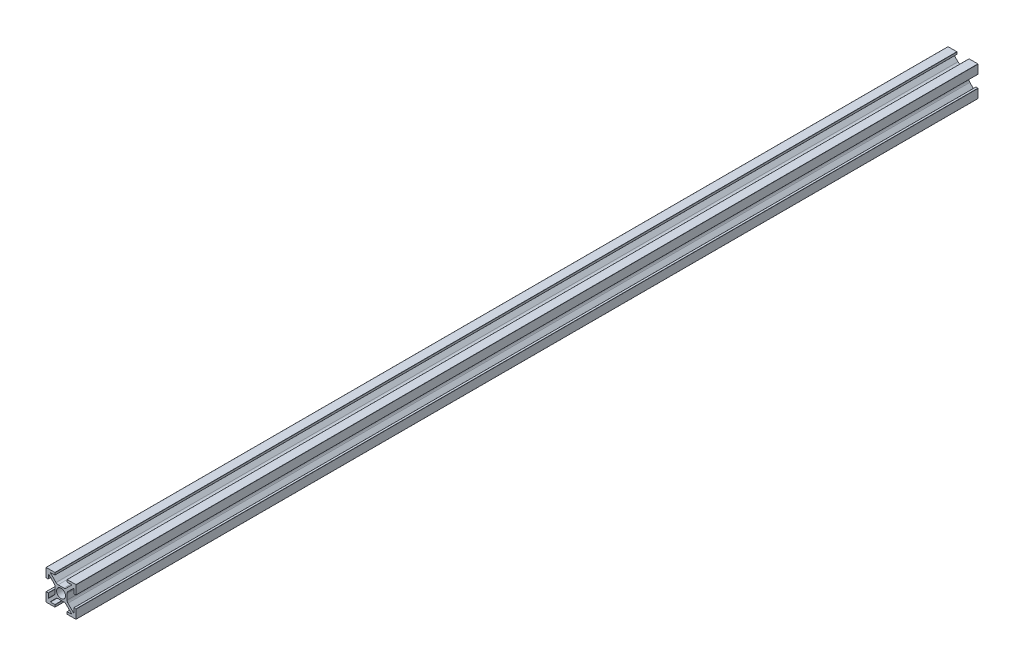
SolidWorks part; units mm, degrees
material "6061-T6 (SS)"
ref_plane "Front Plane" through (0, 0, 0) normal (0, 0, 1) x (1, 0, 0)
ref_plane "Top Plane" through (0, 0, 0) normal (0, 1, 0) x (1, 0, 0)
ref_plane "Right Plane" through (0, 0, 0) normal (1, 0, 0) x (0, 0, -1)
ref_plane "Plane1" through (0, 0, 60) normal (0, 0, 1) x (1, 0, 0)
sketch "Sketch1" plane through (0, 0, 60) normal (0, 0, 1) x (1, 0, 0)
  line L0 (18.5, 17.0086) -> (18.5, 14.1)
  line L1 (18.6, 14) -> (19.9, 14)
  line L2 (20, 14.1) -> (20, 19.9)
  line L3 (19.9, 20) -> (14.1, 20)
  line L4 (14, 19.9) -> (14, 18.6)
  line L5 (14.1, 18.5) -> (17.0086, 18.5)
  line L6 (17.0793, 18.3293) -> (13.3358, 14.5858)
  line L7 (11.9216, 14) -> (8.0784, 14)
  line L8 (6.6642, 14.5858) -> (2.9207, 18.3293)
  line L9 (2.9914, 18.5) -> (5.9, 18.5)
  line L10 (6, 18.6) -> (6, 19.9)
  line L11 (5.9, 20) -> (0.1, 20)
  line L12 (0, 19.9) -> (0, 14.1)
  line L13 (0.1, 14) -> (1.4, 14)
  line L14 (1.5, 14.1) -> (1.5, 17.0086)
  line L15 (1.6707, 17.0793) -> (5.4142, 13.3358)
  line L16 (6, 11.9216) -> (6, 8.0784)
  line L17 (5.4142, 6.6642) -> (1.6707, 2.9207)
  line L18 (1.5, 2.9914) -> (1.5, 5.9)
  line L19 (1.4, 6) -> (0.1, 6)
  line L20 (0, 5.9) -> (0, 0.1)
  line L21 (0.1, 0) -> (5.9, 0)
  line L22 (6, 0.1) -> (6, 1.4)
  line L23 (5.9, 1.5) -> (2.9914, 1.5)
  line L24 (2.9207, 1.6707) -> (6.6642, 5.4142)
  line L25 (8.0784, 6) -> (11.9216, 6)
  line L26 (13.3358, 5.4142) -> (17.0793, 1.6707)
  line L27 (17.0086, 1.5) -> (14.1, 1.5)
  line L28 (14, 1.4) -> (14, 0.1)
  line L29 (14.1, 0) -> (19.9, 0)
  line L30 (20, 0.1) -> (20, 5.9)
  line L31 (19.9, 6) -> (18.6, 6)
  line L32 (18.5, 5.9) -> (18.5, 2.9914)
  line L33 (18.3293, 2.9207) -> (14.5858, 6.6642)
  line L34 (14, 8.0784) -> (14, 11.9216)
  line L35 (14.5858, 13.3358) -> (18.3293, 17.0793)
  circle A0 centre (10, 10) radius 3
  arc A1 (18.3293, 17.0793) -> (18.5, 17.0086) centre (18.4, 17.0086) cw
  arc A2 (18.5, 14.1) -> (18.6, 14) centre (18.6, 14.1) ccw
  arc A3 (19.9, 14) -> (20, 14.1) centre (19.9, 14.1) ccw
  arc A4 (20, 19.9) -> (19.9, 20) centre (19.9, 19.9) ccw
  arc A5 (14.1, 20) -> (14, 19.9) centre (14.1, 19.9) ccw
  arc A6 (14, 18.6) -> (14.1, 18.5) centre (14.1, 18.6) ccw
  arc A7 (17.0086, 18.5) -> (17.0793, 18.3293) centre (17.0086, 18.4) cw
  arc A8 (13.3358, 14.5858) -> (11.9216, 14) centre (11.9216, 16) cw
  arc A9 (8.0784, 14) -> (6.6642, 14.5858) centre (8.0784, 16) cw
  arc A10 (2.9207, 18.3293) -> (2.9914, 18.5) centre (2.9914, 18.4) cw
  arc A11 (5.9, 18.5) -> (6, 18.6) centre (5.9, 18.6) ccw
  arc A12 (6, 19.9) -> (5.9, 20) centre (5.9, 19.9) ccw
  arc A13 (0.1, 20) -> (0, 19.9) centre (0.1, 19.9) ccw
  arc A14 (0, 14.1) -> (0.1, 14) centre (0.1, 14.1) ccw
  arc A15 (1.4, 14) -> (1.5, 14.1) centre (1.4, 14.1) ccw
  arc A16 (1.5, 17.0086) -> (1.6707, 17.0793) centre (1.6, 17.0086) cw
  arc A17 (5.4142, 13.3358) -> (6, 11.9216) centre (4, 11.9216) cw
  arc A18 (6, 8.0784) -> (5.4142, 6.6642) centre (4, 8.0784) cw
  arc A19 (1.6707, 2.9207) -> (1.5, 2.9914) centre (1.6, 2.9914) cw
  arc A20 (1.5, 5.9) -> (1.4, 6) centre (1.4, 5.9) ccw
  arc A21 (0.1, 6) -> (0, 5.9) centre (0.1, 5.9) ccw
  arc A22 (0, 0.1) -> (0.1, 0) centre (0.1, 0.1) ccw
  arc A23 (5.9, 0) -> (6, 0.1) centre (5.9, 0.1) ccw
  arc A24 (6, 1.4) -> (5.9, 1.5) centre (5.9, 1.4) ccw
  arc A25 (2.9914, 1.5) -> (2.9207, 1.6707) centre (2.9914, 1.6) cw
  arc A26 (6.6642, 5.4142) -> (8.0784, 6) centre (8.0784, 4) cw
  arc A27 (11.9216, 6) -> (13.3358, 5.4142) centre (11.9216, 4) cw
  arc A28 (17.0793, 1.6707) -> (17.0086, 1.5) centre (17.0086, 1.6) cw
  arc A29 (14.1, 1.5) -> (14, 1.4) centre (14.1, 1.4) ccw
  arc A30 (14, 0.1) -> (14.1, 0) centre (14.1, 0.1) ccw
  arc A31 (19.9, 0) -> (20, 0.1) centre (19.9, 0.1) ccw
  arc A32 (20, 5.9) -> (19.9, 6) centre (19.9, 5.9) ccw
  arc A33 (18.6, 6) -> (18.5, 5.9) centre (18.6, 5.9) ccw
  arc A34 (18.5, 2.9914) -> (18.3293, 2.9207) centre (18.4, 2.9914) cw
  arc A35 (14.5858, 6.6642) -> (14, 8.0784) centre (16, 8.0784) cw
  arc A36 (14, 11.9216) -> (14.5858, 13.3358) centre (16, 11.9216) cw
extrude "Boss-Extrude2" add sketch "Sketch1" along normal blind 600
